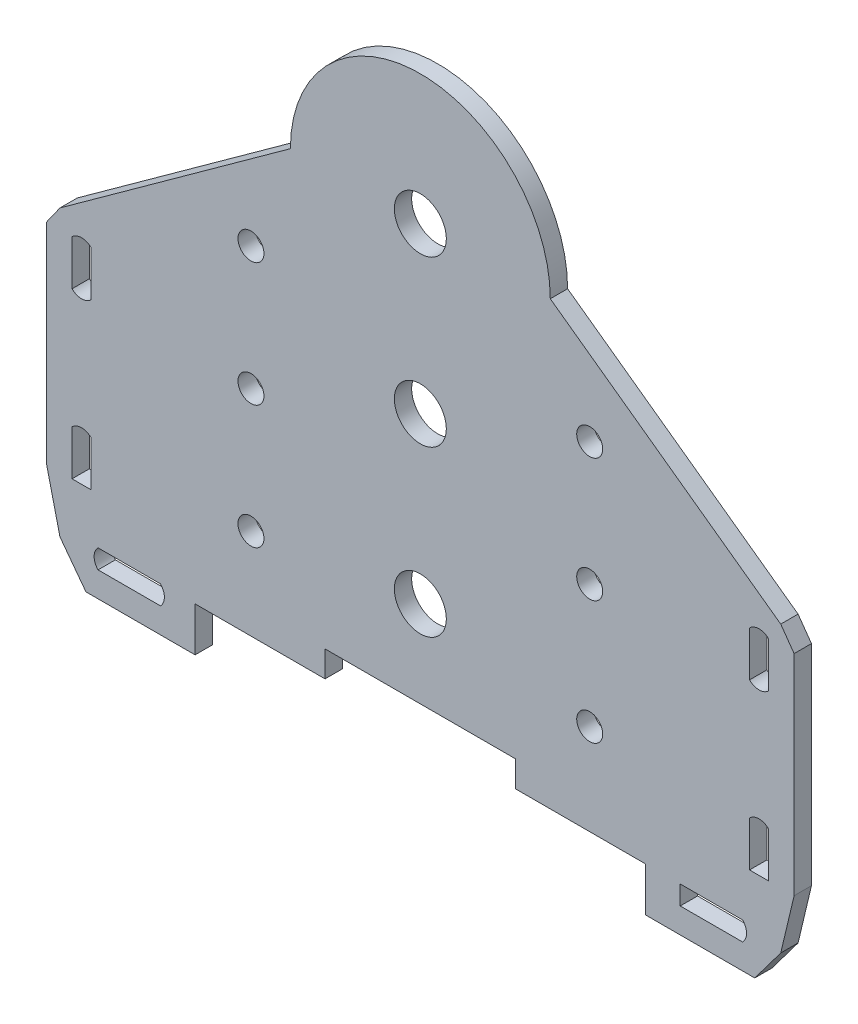
SolidWorks part; units mm, degrees
ref_plane "前视基准面" through (0, 0, 0) normal (0, 0, 1) x (1, 0, 0)
ref_plane "上视基准面" through (0, 0, 0) normal (0, 1, 0) x (1, 0, 0)
ref_plane "右视基准面" through (0, 0, 0) normal (1, 0, 0) x (0, 0, -1)
sketch "草图1" plane through (0, 0, 0) normal (0, 0, 1) x (1, 0, 0)
  line L0 (-33.6, -4) -> (-26, -4)
  line L1 (-30, 0) -> (-33.6, 0) construction
  line L2 (0, 0) -> (0, 5.4028) construction
  line L3 (37.2, 1.1) -> (30, -1.1) construction
  line L8 (-37.2, -1.1) -> (-30, 1.1) construction
  line L9 (-37.2, 1.1) -> (-30, -1.1) construction
  line L10 (37.2, -1.1) -> (30, 1.1) construction
  line L11 (30, 0) -> (33.6, 0) construction
  line L13 (37.2, 1.1) -> (30, 1.1)
  line L15 (37.2, -1.1) -> (30, -1.1)
  line L16 (26, 1.1) -> (26, -4)
  line L21 (-37.2, -1.1) -> (-30, -1.1)
  line L23 (-37.2, 1.1) -> (-30, 1.1)
  line L30 (33.6, -4) -> (38.6, -4)
  line L31 (38.6, -4) -> (41.6, 0)
  line L33 (-38.6, -4) -> (-41.6, 0)
  line L34 (-33.6, -4) -> (-38.6, -4)
  line L39 (-26, 1.1) -> (26, 1.1) construction
  line L43 (-26, 1.1) -> (-11, 1.1)
  line L44 (-11, 1.1) -> (-11, 4.1)
  line L45 (-11, 4.1) -> (11, 4.1)
  line L46 (11, 1.1) -> (11, 4.1)
  line L47 (26, 1.1) -> (11, 1.1)
  line L48 (40.2, 6.5) -> (38, 11.7) construction
  line L53 (-26, -4) -> (-26, 1.1)
  line L54 (26, -4) -> (33.6, -4)
  line L55 (40.2, 11.7) -> (38, 6.5) construction
  line L57 (38, 30.7) -> (40.2, 25.5) construction
  line L58 (-38, 25.5) -> (-38, 30.7)
  line L60 (-40.2, 25.5) -> (-40.2, 30.7)
  line L61 (-38, 25.5) -> (-40.2, 30.7) construction
  line L62 (-38, 30.7) -> (-40.2, 25.5) construction
  line L64 (-40.2, 11.7) -> (-40.2, 6.5)
  line L66 (-38, 11.7) -> (-38, 6.5)
  line L67 (-40.2, 11.7) -> (-38, 6.5) construction
  line L68 (-40.2, 6.5) -> (-38, 11.7) construction
  line L71 (-43.1457, 6.5) -> (-43.1457, 30.7)
  line L72 (-43.1457, 30.7) -> (-41.6, 32.8775)
  line L73 (-41.6, 32.8775) -> (-15, 52.1)
  line L75 (38, 25.5) -> (40.2, 30.7) construction
  line L76 (43.1457, 30.7) -> (41.6, 32.8775)
  line L77 (43.1457, 6.5) -> (43.1457, 30.7)
  line L79 (38, 11.7) -> (38, 6.5)
  line L81 (40.2, 11.7) -> (40.2, 6.5)
  line L83 (40.2, 25.5) -> (40.2, 30.7)
  line L85 (38, 25.5) -> (38, 30.7)
  line L88 (41.6, 32.8775) -> (15, 52.1)
  line L89 (-43.1457, 6.5) -> (-41.6, 0)
  line L90 (41.6, 0) -> (43.1457, 6.5)
  line L91 (-40.2, 6.5) -> (-38, 6.5)
  line L92 (38, 6.5) -> (40.2, 6.5)
  line L93 (30, 1.1) -> (30, -1.1)
  line L94 (0, 52.1) -> (-39.1, 28.1) construction
  line L95 (-39.1, 28.1) -> (-39.1, 9.1) construction
  line L96 (0, 33.1) -> (-39.1, 18.6) construction
  line L97 (0, 14.1) -> (-39.1, 9.1) construction
  circle A2 centre (0, 14.1) radius 3
  circle A3 centre (0, 33.1) radius 3
  circle A4 centre (0, 52.1) radius 3
  arc A5 (15, 52.1) -> (-15, 52.1) centre (0, 52.1) ccw
  arc A6 (-37.2, -1.1) -> (-37.2, 1.1) centre (-36.1, 0) cw
  arc A7 (-30, 1.1) -> (-30, -1.1) centre (-31.1, 0) cw
  arc A9 (37.2, 1.1) -> (37.2, -1.1) centre (36.1, 0) cw
  arc A10 (38, 11.7) -> (40.2, 11.7) centre (39.1, 10.6) cw
  arc A12 (40.2, 25.5) -> (38, 25.5) centre (39.1, 26.6) cw
  arc A13 (38, 30.7) -> (40.2, 30.7) centre (39.1, 29.6) cw
  arc A14 (-40.2, 30.7) -> (-38, 30.7) centre (-39.1, 29.6) cw
  arc A15 (-40.2, 25.5) -> (-38, 25.5) centre (-39.1, 26.6) ccw
  arc A16 (-40.2, 11.7) -> (-38, 11.7) centre (-39.1, 10.6) cw
  circle A17 centre (-19.55, 40.1) radius 1.5
  circle A18 centre (-19.55, 25.85) radius 1.5
  circle A19 centre (-19.55, 11.6) radius 1.5
  circle A20 centre (19.55, 11.6) radius 1.5
  circle A21 centre (19.55, 25.85) radius 1.5
  circle A22 centre (19.55, 40.1) radius 1.5
  point P32 (0, 1.1)
  point P36 (0, 4.1)
  point P51 (-39.1, 9.1)
  point P64 (39.1, 9.1)
extrude "凸台-拉伸1" add sketch "草图1" along normal blind 2
sketch "草图2" plane through (0, 0, 2) normal (0, 0, 1) x (1, 0, 0)
  line L0 (0, 14.1) -> (0, 8.1)
  line L1 (0, 8.1) -> (15, 8.1)
  line L2 (15, 8.1) -> (15, 23.1)
  point P0 (0, 14.1)
sketch "草图3" plane through (0, 0, 0) normal (0, 0, -1) x (-1, 0, 0)
  line L0 (0, 14.1) -> (0, 8.1)
  line L1 (0, 8.1) -> (-15, 8.1)
  line L2 (-15, 8.1) -> (-15, 23.1)
